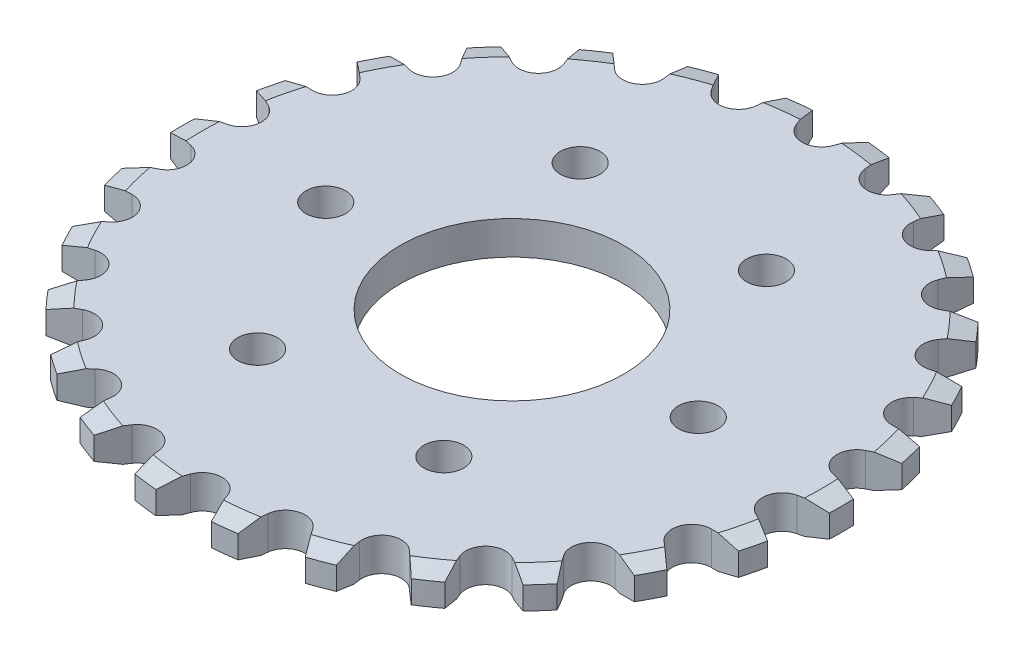
SolidWorks part; units mm, degrees
material "Cast Alloy Steel"
ref_plane "Front Plane" through (0, 0, 0) normal (0, 0, 1) x (1, 0, 0)
ref_plane "Top Plane" through (0, 0, 0) normal (0, 1, 0) x (1, 0, 0)
ref_plane "Right Plane" through (0, 0, 0) normal (1, 0, 0) x (0, 0, -1)
sketch "Sketch1" plane through (0, 0, 0) normal (0, 1, 0) x (1, 0, 0)
  circle A0 centre (0, 0) radius 42.1386
  circle A1 centre (0, 0) radius 14.2812
  dimension "D1" = 84.2772
  dimension "D2" = 28.5623
extrude "Boss-Extrude1" add sketch "Sketch1" along normal blind 4.2672
sketch "Sketch2" plane through (0, 4.2672, 0) normal (0, 1, 0) x (1, 0, 0)
  circle A0 centre (0, 0) radius 23.8125 construction
  circle A1 centre (-23.8125, 0) radius 2.54
  circle A2 centre (-11.9063, 20.6222) radius 2.54
  circle A3 centre (11.9062, 20.6222) radius 2.54
  circle A4 centre (23.8125, 0) radius 2.54
  circle A5 centre (11.9063, -20.6222) radius 2.54
  circle A6 centre (-11.9062, -20.6222) radius 2.54
  point P18 (0, 0)
  dimension "D1" = 47.625
  dimension "D2" = 5.08
  dimension "D3" = 6
extrude "Cut-Extrude1" cut sketch "Sketch2" against normal through all
chamfer "Chamfer1" distance 2.54 angle 15 2 edges at (0, 0, 42.1386) (0, 4.2672, 42.1386)
sketch "Sketch3" plane through (0, 4.2672, 0) normal (0, 1, 0) x (1, 0, 0)
  line L0 (0, 42.1386) -> (0, -42.1386) construction
  line L1 (2.363, 38.7386) -> (3.5461, 41.9891)
  line L2 (-2.363, 38.7386) -> (-3.5461, 41.9891)
  line L3 (6.9765, 38.1784) -> (6.6056, 41.6176)
  line L4 (11.565, 37.0474) -> (13.4917, 39.9204)
  line L5 (15.9104, 35.3994) -> (16.3734, 38.8275)
  line L6 (20.095, 33.2032) -> (22.6532, 35.5316)
  line L7 (23.9197, 30.5632) -> (25.1897, 33.7808)
  line L8 (27.4571, 27.4293) -> (30.4982, 29.0778)
  line L9 (30.5389, 23.9507) -> (32.542, 26.7709)
  line L10 (33.2235, 20.0613) -> (36.5708, 20.9342)
  line L11 (35.3833, 15.9463) -> (38.0031, 18.2052)
  line L12 (37.0591, 11.5275) -> (40.518, 11.5739)
  line L13 (38.1713, 7.0151) -> (41.2556, 8.5814)
  line L14 (38.7409, 2.3237) -> (42.1104, 1.541)
  line L15 (38.7409, -2.3237) -> (42.1104, -1.541)
  line L16 (38.1713, -7.0151) -> (41.2556, -8.5814)
  line L17 (37.0591, -11.5275) -> (40.518, -11.5739)
  line L18 (35.3833, -15.9463) -> (38.0031, -18.2052)
  line L19 (33.2235, -20.0613) -> (36.5708, -20.9342)
  line L20 (30.5389, -23.9507) -> (32.542, -26.7709)
  line L21 (27.4571, -27.4293) -> (30.4982, -29.0778)
  line L22 (23.9197, -30.5632) -> (25.1897, -33.7808)
  line L23 (20.095, -33.2032) -> (22.6532, -35.5316)
  line L24 (15.9104, -35.3994) -> (16.3734, -38.8275)
  line L25 (11.565, -37.0474) -> (13.4917, -39.9204)
  line L26 (6.9765, -38.1784) -> (6.6056, -41.6176)
  line L27 (2.363, -38.7386) -> (3.5461, -41.9891)
  line L28 (-2.363, -38.7386) -> (-3.5461, -41.9891)
  line L29 (-6.9765, -38.1784) -> (-6.6056, -41.6176)
  line L30 (-11.565, -37.0474) -> (-13.4917, -39.9204)
  line L31 (-15.9104, -35.3994) -> (-16.3734, -38.8275)
  line L32 (-20.095, -33.2032) -> (-22.6532, -35.5316)
  line L33 (-23.9197, -30.5632) -> (-25.1897, -33.7808)
  line L34 (-27.4571, -27.4293) -> (-30.4982, -29.0778)
  line L35 (-30.5389, -23.9507) -> (-32.542, -26.7709)
  line L36 (-33.2235, -20.0613) -> (-36.5708, -20.9342)
  line L37 (-35.3833, -15.9463) -> (-38.0031, -18.2052)
  line L38 (-37.0591, -11.5275) -> (-40.518, -11.5739)
  line L39 (-38.1713, -7.0151) -> (-41.2556, -8.5814)
  line L40 (-38.7409, -2.3237) -> (-42.1104, -1.541)
  line L41 (-38.7409, 2.3237) -> (-42.1104, 1.541)
  line L42 (-38.1713, 7.0151) -> (-41.2556, 8.5814)
  line L43 (-37.0591, 11.5275) -> (-40.518, 11.5739)
  line L44 (-35.3833, 15.9463) -> (-38.0031, 18.2052)
  line L45 (-33.2235, 20.0613) -> (-36.5708, 20.9342)
  line L46 (-30.5389, 23.9507) -> (-32.542, 26.7709)
  line L47 (-27.4571, 27.4293) -> (-30.4982, 29.0778)
  line L48 (-23.9197, 30.5632) -> (-25.1897, 33.7808)
  line L49 (-20.095, 33.2032) -> (-22.6532, 35.5316)
  line L50 (-15.9104, 35.3994) -> (-16.3734, 38.8275)
  line L51 (-11.565, 37.0474) -> (-13.4917, 39.9204)
  line L52 (-6.9765, 38.1784) -> (-6.6056, 41.6176)
  circle A0 centre (0, 0) radius 39.5986 construction
  circle A1 centre (0, 0) radius 42.1386 construction
  arc A2 (-2.363, 38.7386) -> (2.363, 38.7386) centre (0, 39.5986) ccw
  arc A3 (3.5461, 41.9891) -> (-3.5461, 41.9891) centre (0, 0) ccw
  arc A4 (6.9765, 38.1784) -> (11.565, 37.0474) centre (9.4766, 38.4479) ccw
  arc A5 (13.4917, 39.9204) -> (6.6056, 41.6176) centre (0, 0) ccw
  arc A6 (15.9104, 35.3994) -> (20.095, 33.2032) centre (18.4024, 35.0628) ccw
  arc A7 (22.6532, 35.5316) -> (16.3734, 38.8275) centre (0, 0) ccw
  arc A8 (23.9197, 30.5632) -> (27.4571, 27.4293) centre (26.2587, 29.64) ccw
  arc A9 (30.4982, 29.0778) -> (25.1897, 33.7808) centre (0, 0) ccw
  arc A10 (30.5389, 23.9507) -> (33.2235, 20.0613) centre (32.589, 22.4946) ccw
  arc A11 (36.5708, 20.9342) -> (32.542, 26.7709) centre (0, 0) ccw
  arc A12 (35.3833, 15.9463) -> (37.0591, 11.5275) centre (37.0253, 14.0419) ccw
  arc A13 (40.518, 11.5739) -> (38.0031, 18.2052) centre (0, 0) ccw
  arc A14 (38.1713, 7.0151) -> (38.7409, 2.3237) centre (39.3099, 4.7731) ccw
  arc A15 (42.1104, 1.541) -> (41.2556, 8.5814) centre (0, 0) ccw
  arc A16 (38.7409, -2.3237) -> (38.1713, -7.0151) centre (39.3099, -4.7731) ccw
  arc A17 (41.2556, -8.5814) -> (42.1104, -1.541) centre (0, 0) ccw
  arc A18 (37.0591, -11.5275) -> (35.3833, -15.9463) centre (37.0253, -14.0419) ccw
  arc A19 (38.0031, -18.2052) -> (40.518, -11.5739) centre (0, 0) ccw
  arc A20 (33.2235, -20.0613) -> (30.5389, -23.9507) centre (32.589, -22.4946) ccw
  arc A21 (32.542, -26.7709) -> (36.5708, -20.9342) centre (0, 0) ccw
  arc A22 (27.4571, -27.4293) -> (23.9197, -30.5632) centre (26.2587, -29.64) ccw
  arc A23 (25.1897, -33.7808) -> (30.4982, -29.0778) centre (0, 0) ccw
  arc A24 (20.095, -33.2032) -> (15.9104, -35.3994) centre (18.4024, -35.0628) ccw
  arc A25 (16.3734, -38.8275) -> (22.6532, -35.5316) centre (0, 0) ccw
  arc A26 (11.565, -37.0474) -> (6.9765, -38.1784) centre (9.4766, -38.4479) ccw
  arc A27 (6.6056, -41.6176) -> (13.4917, -39.9204) centre (0, 0) ccw
  arc A28 (2.363, -38.7386) -> (-2.363, -38.7386) centre (0, -39.5986) ccw
  arc A29 (-3.5461, -41.9891) -> (3.5461, -41.9891) centre (0, 0) ccw
  arc A30 (-6.9765, -38.1784) -> (-11.565, -37.0474) centre (-9.4766, -38.4479) ccw
  arc A31 (-13.4917, -39.9204) -> (-6.6056, -41.6176) centre (0, 0) ccw
  arc A32 (-15.9104, -35.3994) -> (-20.095, -33.2032) centre (-18.4024, -35.0628) ccw
  arc A33 (-22.6532, -35.5316) -> (-16.3734, -38.8275) centre (0, 0) ccw
  arc A34 (-23.9197, -30.5632) -> (-27.4571, -27.4293) centre (-26.2587, -29.64) ccw
  arc A35 (-30.4982, -29.0778) -> (-25.1897, -33.7808) centre (0, 0) ccw
  arc A36 (-30.5389, -23.9507) -> (-33.2235, -20.0613) centre (-32.589, -22.4946) ccw
  arc A37 (-36.5708, -20.9342) -> (-32.542, -26.7709) centre (0, 0) ccw
  arc A38 (-35.3833, -15.9463) -> (-37.0591, -11.5275) centre (-37.0253, -14.0419) ccw
  arc A39 (-40.518, -11.5739) -> (-38.0031, -18.2052) centre (0, 0) ccw
  arc A40 (-38.1713, -7.0151) -> (-38.7409, -2.3237) centre (-39.3099, -4.7731) ccw
  arc A41 (-42.1104, -1.541) -> (-41.2556, -8.5814) centre (0, 0) ccw
  arc A42 (-38.7409, 2.3237) -> (-38.1713, 7.0151) centre (-39.3099, 4.7731) ccw
  arc A43 (-41.2556, 8.5814) -> (-42.1104, 1.541) centre (0, 0) ccw
  arc A44 (-37.0591, 11.5275) -> (-35.3833, 15.9463) centre (-37.0253, 14.0419) ccw
  arc A45 (-38.0031, 18.2052) -> (-40.518, 11.5739) centre (0, 0) ccw
  arc A46 (-33.2235, 20.0613) -> (-30.5389, 23.9507) centre (-32.589, 22.4946) ccw
  arc A47 (-32.542, 26.7709) -> (-36.5708, 20.9342) centre (0, 0) ccw
  arc A48 (-27.4571, 27.4293) -> (-23.9197, 30.5632) centre (-26.2587, 29.64) ccw
  arc A49 (-25.1897, 33.7808) -> (-30.4982, 29.0778) centre (0, 0) ccw
  arc A50 (-20.095, 33.2032) -> (-15.9104, 35.3994) centre (-18.4024, 35.0628) ccw
  arc A51 (-16.3734, 38.8275) -> (-22.6532, 35.5316) centre (0, 0) ccw
  arc A52 (-11.565, 37.0474) -> (-6.9765, 38.1784) centre (-9.4766, 38.4479) ccw
  arc A53 (-6.6056, 41.6176) -> (-13.4917, 39.9204) centre (0, 0) ccw
  point P121 (0, 0)
  dimension "D1" = 79.1972
  dimension "D3" = 2.5146
  dimension "D2" = 20
  dimension "D4" = 26
extrude "Cut-Extrude2" cut sketch "Sketch3" against normal through all
